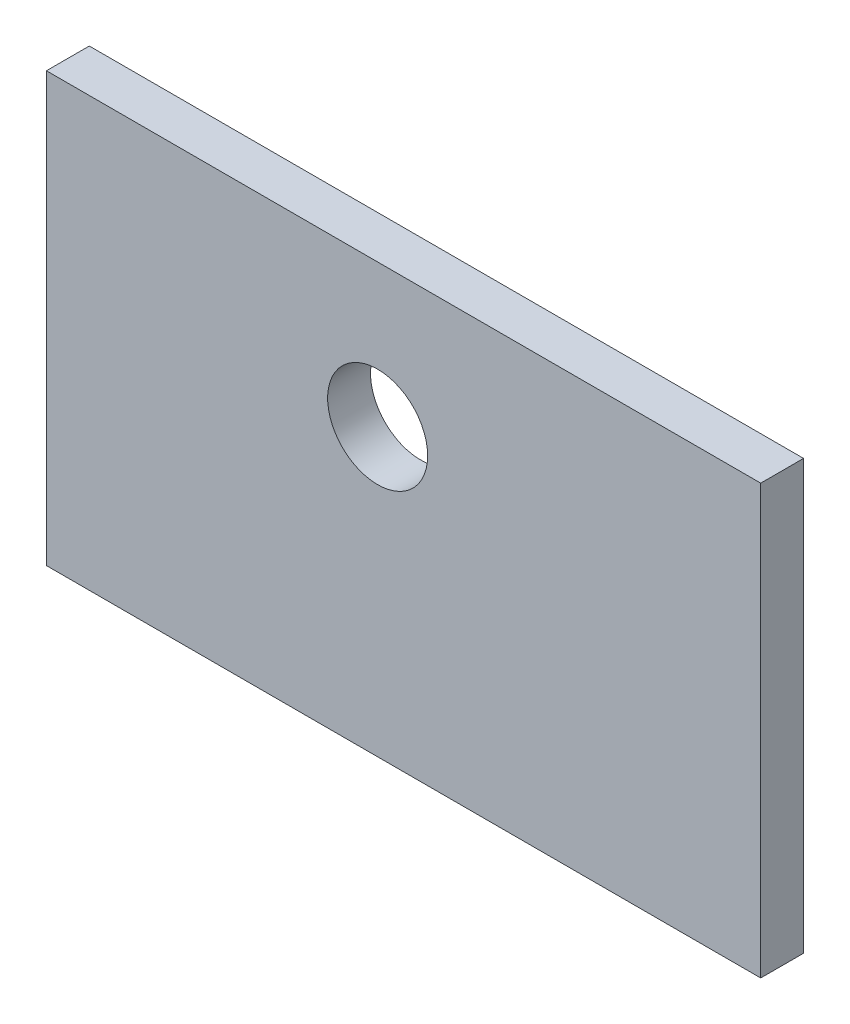
SolidWorks part; units mm, degrees
ref_plane "Plan de face" through (0, 0, 0) normal (0, 0, 1) x (1, 0, 0)
ref_plane "Plan de dessus" through (0, 0, 0) normal (0, 1, 0) x (1, 0, 0)
ref_plane "Plan de droite" through (0, 0, 0) normal (1, 0, 0) x (0, 0, -1)
sketch "Esquisse1" plane through (0, 0, 0) normal (0, 0, 1) x (1, 0, 0)
  line L1 (0, 0) -> (50, 0)
  line L2 (0, 0) -> (0, 30)
  line L3 (0, 30) -> (50, 30)
  line L4 (50, 0) -> (50, 30)
  circle A0 centre (23.185, 20) radius 3.5
  dimension "D3" = 7
  dimension "D4" = 10
  dimension "D1" = 50
  dimension "D2" = 30
extrude "Boss.-Extru.1" add sketch "Esquisse1" along normal blind 3
